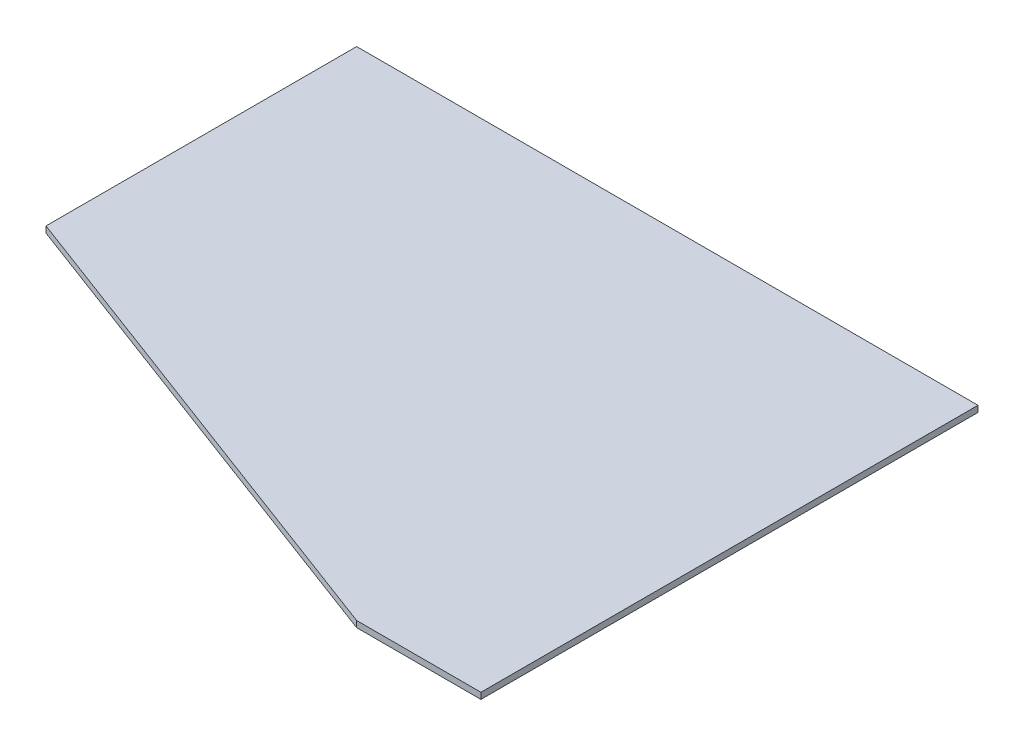
SolidWorks part; units mm, degrees
material "Бук"
ref_plane "Спереди" through (0, 0, 0) normal (0, 0, 1) x (1, 0, 0)
ref_plane "Сверху" through (0, 0, 0) normal (0, 1, 0) x (1, 0, 0)
ref_plane "Справа" through (0, 0, 0) normal (1, 0, 0) x (0, 0, -1)
sketch "Эскиз1" plane through (0, 0, 0) normal (0, 1, 0) x (1, 0, 0)
  line L1 (1300, 0) -> (1500, 0)
  line L2 (500, 300) -> (500, 800)
  line L3 (500, 800) -> (1500, 800)
  line L4 (1500, 0) -> (1500, 800)
  line L5 (1300, 0) -> (500, 300)
  dimension "D1" = 1000
  dimension "D2" = 800
  dimension "D3" = 500
  dimension "D4" = 200
extrude "Бобышка-Вытянуть1" add sketch "Эскиз1" along normal blind 10
sketch "Эскиз2" plane through (0, 0, 0) normal (0, -1, 0) x (1, 0, 0)
  line L0 (1400, -800) -> (1400, 0) construction
  line L1 (1500, -800) -> (500, -800) construction
  line L2 (1300, 0) -> (1500, 0) construction
  line L3 (1500, 0) -> (1500, -800) construction
  circle A0 centre (1400, -120) radius 40
  circle A1 centre (1400, -700) radius 40
  dimension "D2" = 80
  dimension "D3" = 80
  dimension "D1" = 100
  dimension "D4" = 120
  dimension "D5" = 100
extrude "Вырез-Вытянуть1" cut sketch "Эскиз2" against normal blind 5
